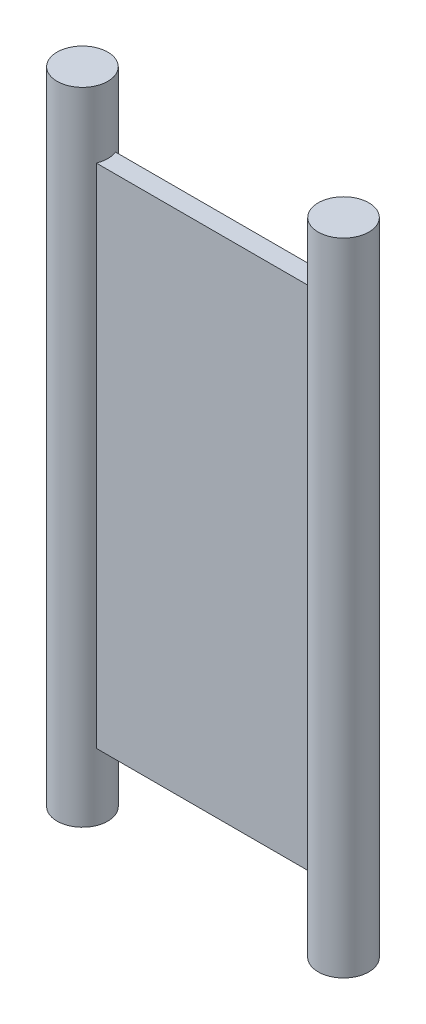
SolidWorks part; units mm, degrees
ref_plane "Front Plane" through (0, 0, 0) normal (0, 0, 1) x (1, 0, 0)
ref_plane "Top Plane" through (0, 0, 0) normal (0, 1, 0) x (1, 0, 0)
ref_plane "Right Plane" through (0, 0, 0) normal (1, 0, 0) x (0, 0, -1)
sketch "Sketch1" plane through (0, 0, 0) normal (0, 1, 0) x (1, 0, 0)
  line L1 (6.825, 0.5) -> (-6.825, 0.5)
  line L2 (6.825, 0.5) -> (6.825, -0.5)
  line L3 (6.825, -0.5) -> (-6.825, -0.5)
  line L4 (-6.825, 0.5) -> (-6.825, -0.5)
  line L5 (6.825, 0.5) -> (-6.825, -0.5) construction
  line L6 (6.825, -0.5) -> (-6.825, 0.5) construction
  point P0 (0, 0)
  dimension "D1" = 13.65
  dimension "D3" = 1
extrude "Boss-Extrude1" add sketch "Sketch1" along normal blind 26.5
ref_plane "Plane1" through (0, 13.25, 0) normal (0, 1, 0) x (1, 0, 0)
sketch "Sketch2" plane through (0, 13.25, 0) normal (0, 1, 0) x (1, 0, 0)
  line L0 (6.825, -0.5) -> (6.825, 0.5) construction
  line L1 (-6.825, 0.5) -> (-6.825, -0.5) construction
  line L2 (6.825, -0.5) -> (6.825, 0.5) construction
  line L3 (-6.825, 0.5) -> (-6.825, -0.5) construction
  circle A0 centre (-6.825, 0) radius 1.325
  circle A1 centre (6.825, 0) radius 1.325
  dimension "D1" = 2.65
extrude "Boss-Extrude2" add sketch "Sketch2" along normal mid plane 33.5
